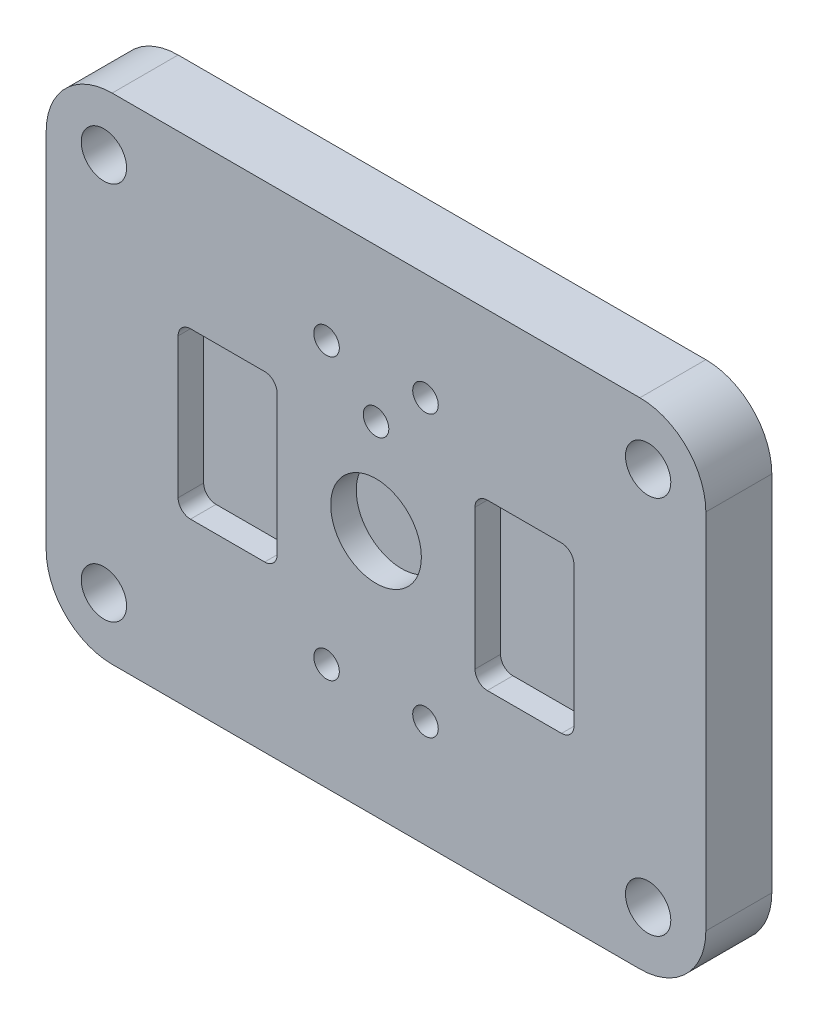
SolidWorks part; units mm, degrees
ref_plane "正面" through (0, 0, 0) normal (0, 0, 1) x (1, 0, 0)
ref_plane "平面" through (0, 0, 0) normal (0, 1, 0) x (1, 0, 0)
ref_plane "右側面" through (0, 0, 0) normal (1, 0, 0) x (0, 0, -1)
sketch "ｽｹｯﾁ1" plane through (0, 0, 0) normal (0, 0, 1) x (1, 0, 0)
  line L1 (0, 0) -> (47.3, 0)
  line L2 (0, 0) -> (0, 47.3)
  line L3 (0, 47.3) -> (47.3, 47.3)
  line L4 (47.3, 0) -> (47.3, 47.3)
  line L5 (-16.35, 53.65) -> (63.65, 53.65)
  line L6 (-16.35, 53.65) -> (-16.35, -6.35)
  line L7 (-16.35, -6.35) -> (63.65, -6.35)
  line L8 (63.65, 53.65) -> (63.65, -6.35)
  dimension "D1" = 47.3
  dimension "D2" = 47.3
  dimension "D3" = 80
  dimension "D4" = 60
  dimension "D5" = 16.35
  dimension "D6" = 6.35
extrude "ﾎﾞｽ - 押し出し1" add sketch "ｽｹｯﾁ1" along normal blind 8 contours L1 L4 L3 L2 | L8 L5 L6 L7 L4 L1 L2 L3
sketch "ｽｹｯﾁ2" plane through (0, 0, 8) normal (0, 0, 1) x (1, 0, 0)
  line L1 (-0.35, 33.65) -> (11.65, 33.65)
  line L2 (-0.35, 33.65) -> (-0.35, 13.65)
  line L3 (-0.35, 13.65) -> (11.65, 13.65)
  line L4 (11.65, 33.65) -> (11.65, 13.65)
  line L8 (47.65, 33.65) -> (35.65, 33.65)
  line L9 (47.65, 33.65) -> (47.65, 13.65)
  line L10 (47.65, 13.65) -> (35.65, 13.65)
  line L11 (35.65, 33.65) -> (35.65, 13.65)
  line L12 (-16.35, 53.65) -> (63.65, 53.65) construction
  line L17 (-16.35, 53.65) -> (-16.35, -6.35) construction
  circle A0 centre (23.65, 23.65) radius 5.5
  circle A1 centre (23.65, 35.15) radius 1.55
  dimension "D1" = 12
  dimension "D6" = 3.1
  dimension "D11" = 11
  dimension "D2" = 20
  dimension "D3" = 30
  dimension "D4" = 12
  dimension "D5" = 10
  dimension "D7" = 12
  dimension "D8" = 12
  dimension "D9" = 20
  dimension "D10" = 40
extrude "ｶｯﾄ - 押し出し1" cut sketch "ｽｹｯﾁ2" against normal blind 3.1
fillet "ﾌｨﾚｯﾄ1" radius 1.5 8 edges at (35.65, 33.65, 6.45) (35.65, 13.65, 6.45) (11.65, 13.65, 6.45) (11.65, 33.65, 6.45) (-0.35, 13.65, 6.45) (-0.35, 33.65, 6.45) (47.65, 13.65, 6.45) (47.65, 33.65, 6.45)
sketch "ｽｹｯﾁ3" plane through (0, 0, 8) normal (0, 0, 1) x (1, 0, 0)
  line L1 (17.65, 40.65) -> (29.65, 40.65)
  line L2 (17.65, 40.65) -> (17.65, 6.65)
  line L3 (17.65, 6.65) -> (29.65, 6.65)
  line L4 (29.65, 40.65) -> (29.65, 6.65)
  line L5 (17.65, 40.65) -> (29.65, 6.65) construction
  line L6 (17.65, 6.65) -> (29.65, 40.65) construction
  circle A0 centre (17.65, 40.65) radius 1.55
  circle A1 centre (29.65, 40.65) radius 1.55
  circle A2 centre (29.65, 6.65) radius 1.55
  circle A3 centre (17.65, 6.65) radius 1.55
  point P0 (23.65, 23.65)
  dimension "D1" = 12
  dimension "D2" = 34
extrude "ｶｯﾄ - 押し出し2" cut sketch "ｽｹｯﾁ3" against normal blind 10 contours A0 | A1 | A2 | A3
fillet "ﾌｨﾚｯﾄ2" radius 8 4 edges at (63.65, -6.35, 4) (63.65, 53.65, 4) (-16.35, -6.35, 4) (-16.35, 53.65, 4)
sketch "ｽｹｯﾁ4" plane through (0, 0, 0) normal (0, 0, -1) x (-1, 0, 0)
  circle A0 centre (-29.65, 40.65) radius 3
  circle A1 centre (-17.65, 40.65) radius 3
  circle A2 centre (-17.65, 6.65) radius 3
  circle A3 centre (-29.65, 6.65) radius 3
  dimension "D1" = 6
  dimension "D2" = 6
  dimension "D3" = 6
  dimension "D4" = 6
extrude "ｶｯﾄ - 押し出し3" cut sketch "ｽｹｯﾁ4" against normal blind 3.1
sketch "ｽｹｯﾁ5" plane through (0, 0, 8) normal (0, 0, 1) x (1, 0, 0)
  line L0 (63.65, 45.65) -> (63.65, 1.65) construction
  line L1 (-9.35, 46.65) -> (56.65, 46.65)
  line L2 (-9.35, 46.65) -> (-9.35, 0.65)
  line L3 (-9.35, 0.65) -> (56.65, 0.65)
  line L4 (56.65, 46.65) -> (56.65, 0.65)
  line L5 (-9.35, 46.65) -> (56.65, 0.65) construction
  line L6 (-9.35, 0.65) -> (56.65, 46.65) construction
  line L7 (-8.35, -6.35) -> (55.65, -6.35) construction
  circle A0 centre (56.65, 0.65) radius 2.75
  circle A1 centre (56.65, 46.65) radius 2.75
  circle A2 centre (-9.35, 46.65) radius 2.75
  circle A3 centre (-9.35, 0.65) radius 2.75
  point P0 (23.65, 23.65)
  dimension "D3" = 5.5
  dimension "D4" = 5.5
  dimension "D5" = 5.5
  dimension "D6" = 5.5
  dimension "D1" = 7
  dimension "D2" = 7
extrude "ｶｯﾄ - 押し出し4" cut sketch "ｽｹｯﾁ5" against normal blind 10 contours A2 | A1 | A0 | A3
